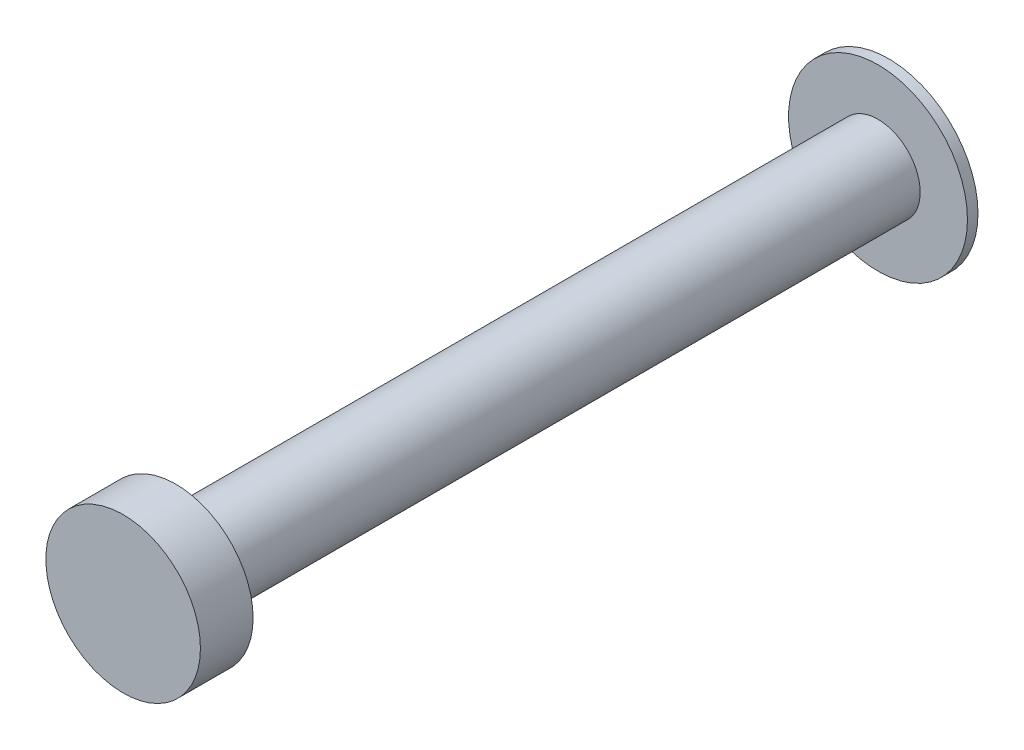
SolidWorks part; units mm, degrees
material "ABS PC"
ref_plane "Front Plane" through (0, 0, 0) normal (0, 0, 1) x (1, 0, 0)
ref_plane "Top Plane" through (0, 0, 0) normal (0, 1, 0) x (1, 0, 0)
ref_plane "Right Plane" through (0, 0, 0) normal (1, 0, 0) x (0, 0, -1)
sketch "Sketch1" plane through (0, 0, 0) normal (0, 1, 0) x (1, 0, 0)
  line L0 (-124.4203, -21.5352) -> (-108.2532, -21.5352)
  line L1 (-108.2532, -21.5352) -> (-108.2532, -23.4402)
  line L2 (-108.2532, -23.4402) -> (-116.8003, -23.4402)
  line L3 (-116.8003, -23.4402) -> (-116.8003, -150.364)
  line L4 (-116.8003, -150.364) -> (-110.4503, -150.364)
  line L5 (-110.4503, -150.364) -> (-110.4503, -159.889)
  line L6 (-110.4503, -159.889) -> (-124.4203, -159.889)
  line L7 (-124.4203, -159.889) -> (-124.4203, -21.5352)
  point P0 (-117.4353, -159.889)
  dimension "D1" = 9.525
  dimension "D2" = 13.97
  dimension "D3" = 1.905
  dimension "D4" = 138.3538
  dimension "D5" = 16.1671
  dimension "D6" = 7.62
revolve "Revolve1" add sketch "Sketch1" angle 360 about L7
